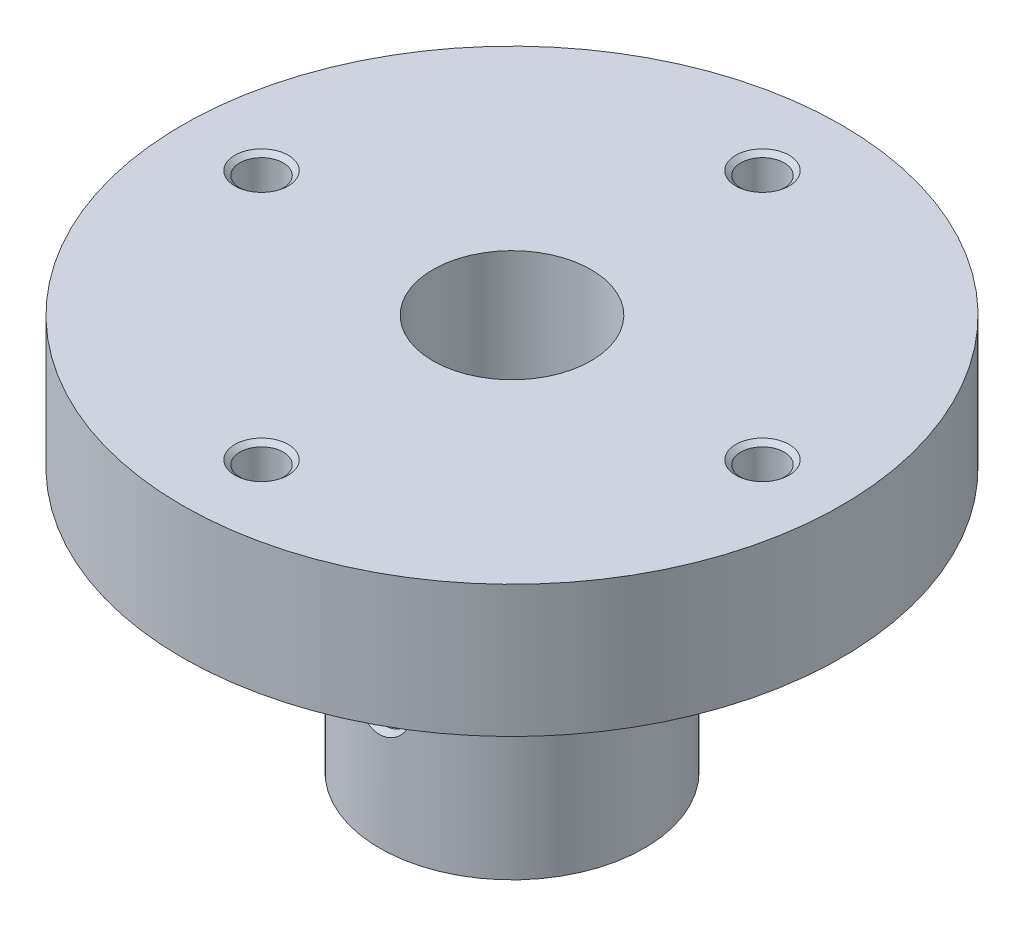
SolidWorks part; units mm, degrees
ref_plane "Front Plane" through (0, 0, 0) normal (0, 0, 1) x (1, 0, 0)
ref_plane "Top Plane" through (0, 0, 0) normal (0, 1, 0) x (1, 0, 0)
ref_plane "Right Plane" through (0, 0, 0) normal (1, 0, 0) x (0, 0, -1)
sketch "Sketch1" plane through (0, 0, 0) normal (0, 1, 0) x (1, 0, 0)
  circle A0 centre (0, 0) radius 25
  dimension "D1" = 50
extrude "Boss-Extrude1" add sketch "Sketch1" along normal blind 10
sketch "Sketch2" plane through (0, 0, 0) normal (0, -1, 0) x (1, 0, 0)
  circle A0 centre (0, 0) radius 10.0372
extrude "Boss-Extrude2" add sketch "Sketch2" along normal blind 20
sketch "Sketch3" plane through (0, 10, 0) normal (0, 1, 0) x (1, 0, 0)
  circle A0 centre (0, 0) radius 6
  dimension "D1" = 12
extrude "Cut-Extrude1" cut sketch "Sketch3" against normal through all
hole_wizard "M4x0.7 Tapped Hole1" positions "Sketch4" profile "Sketch5" tap size "M4x0.7" standard "ANSI Metric"
sketch "Sketch4" plane through (0, 10, 0) normal (0, 1, 0) x (1, 0, 0)
  point P0 (19, 0)
  dimension "D1" = 19
sketch "Sketch5" plane through (19, 10, 0) normal (1, 0, 0) x (0, 0, 1)
  line L0 (0, 0) -> (0, 9.9914)
  line L1 (0, 9.9914) -> (1.65, 9)
  line L2 (1.65, 9) -> (1.65, 0.3147)
  line L3 (1.65, 0.3147) -> (2.025, 0)
  line L5 (2.025, 0) -> (0, 0)
  line L6 (-1.65, 0.3147) -> (-2.025, 0) construction
  line L10 (0, 9.9914) -> (-1.65, 9) construction
  line L11 (0, -6.35) -> (0, 107.95) construction
  dimension "Tap Drill Dia." = 3.3
  dimension "Tap Drill Depth" = 9
  dimension "Near C'Sink Dia." = 4.05
  dimension "Near C'Sink Angle" = 100
  dimension "Drill Angle" = 118
cosmetic thread "Hole Thread1" parameters "D1"=7, "D2"=4
pattern_circular "CirPattern1" count 4 over 360 about axis through (0, 0, 0) along (0, 1, 0) of "M4x0.7 Tapped Hole1"
cosmetic thread "Hole Thread2" parameters "D1"=7, "D2"=4
cosmetic thread "Hole Thread3" parameters "D1"=7, "D2"=4
cosmetic thread "Hole Thread4" parameters "D1"=7, "D2"=4
ref_plane "Plane1" through (0, 0, 10.0372) normal (0, 0, 1) x (1, 0, 0)
hole_wizard "M5x0.8 Tapped Hole1" positions "Sketch7" profile "Sketch8" tap size "M5x0.8" standard "ANSI Metric"
sketch "Sketch7" plane through (0, 0, 10.0372) normal (0, 0, 1) x (1, 0, 0)
  line L0 (0, 0) -> (0, -14.175) construction
  point P0 (0, -10)
  dimension "D1" = 10
sketch "Sketch8" plane through (0, -10, 10.0372) normal (1, 0, 0) x (0, -1, 0)
  line L0 (0, 0) -> (0, 12.2618)
  line L1 (0, 12.2618) -> (2.1, 11)
  line L2 (2.1, 11) -> (2.1, 0.3566)
  line L3 (2.1, 0.3566) -> (2.525, 0)
  line L5 (2.525, 0) -> (0, 0)
  line L6 (-2.1, 0.3566) -> (-2.525, 0) construction
  line L10 (0, 12.2618) -> (-2.1, 11) construction
  line L11 (0, -6.35) -> (0, 107.95) construction
  dimension "Tap Drill Dia." = 4.2
  dimension "Tap Drill Depth" = 11
  dimension "Near C'Sink Dia." = 5.05
  dimension "Near C'Sink Angle" = 100
  dimension "Drill Angle" = 118
cosmetic thread "Hole Thread5" parameters "D1"=8, "D2"=5
